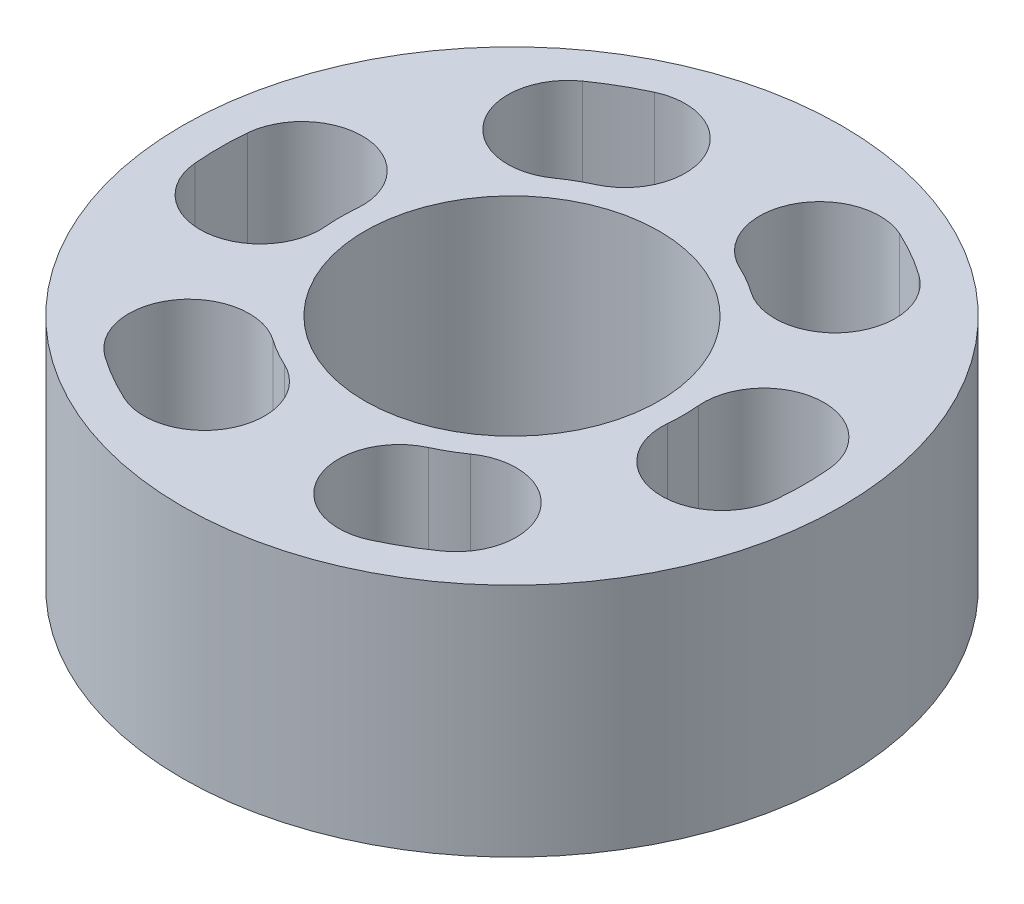
SolidWorks part; units mm, degrees
material "AISI 4130 Steel, normalized at 870C"
ref_plane "Front Plane" through (0, 0, 0) normal (0, 0, 1) x (1, 0, 0)
ref_plane "Top Plane" through (0, 0, 0) normal (0, 1, 0) x (1, 0, 0)
ref_plane "Right Plane" through (0, 0, 0) normal (1, 0, 0) x (0, 0, -1)
sketch "Sketch1" plane through (0, 0, 0) normal (0, 1, 0) x (1, 0, 0)
  circle A0 centre (0, 0) radius 17.78
  circle A1 centre (0, 0) radius 7.9375
  dimension "D1" = 35.56
  dimension "D2" = 15.875
extrude "Boss-Extrude1" add sketch "Sketch1" along normal blind 12.7
sketch "Sketch2" plane through (0, 12.7, 0) normal (0, 1, 0) x (1, 0, 0)
  line L0 (0, 0) -> (8.89, 15.3979) construction
  line L1 (0, 0) -> (0, 17.78) construction
  arc A0 (5.25, 11.3441) -> (7.1992, 10.2187) centre (0, 0) cw construction
  circle A1 centre (0, 0) radius 17.78 construction
  arc A2 (6.615, 14.2935) -> (9.071, 12.8755) centre (0, 0) cw
  arc A3 (3.885, 8.3946) -> (5.3274, 7.5618) centre (0, 0) cw
  arc A4 (6.615, 14.2935) -> (3.885, 8.3946) centre (5.25, 11.3441) ccw
  arc A5 (9.071, 12.8755) -> (5.3274, 7.5618) centre (7.1992, 10.2187) cw
  arc A6 (3.885, 8.3946) -> (5.3274, 7.5618) centre (0, 0) cw construction
  point P4 (6.25, 10.8253)
  point P22 (2, 11.3441)
  dimension "D1" = 12.5
  dimension "D5" = 2
  dimension "D2" = 30
  dimension "D3" = 3.25
  dimension "D4" = 3.25
extrude "Cut-Extrude1" cut sketch "Sketch2" against normal through all
pattern_circular "CirPattern1" count 6 over 360 about axis through (0, 0, 0) along (0, 1, 0) of "Cut-Extrude1"
